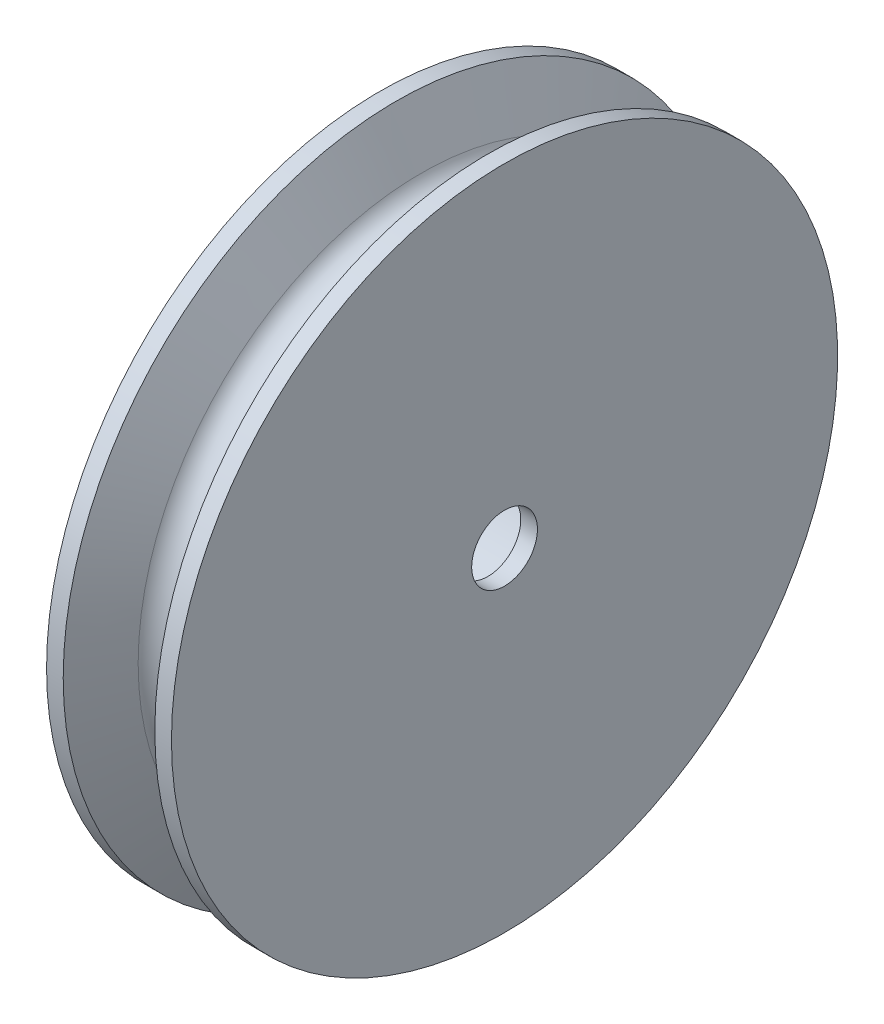
SolidWorks part; units mm, degrees
ref_plane "Alzado" through (0, 0, 0) normal (0, 0, 1) x (1, 0, 0)
ref_plane "Planta" through (0, 0, 0) normal (0, 1, 0) x (1, 0, 0)
ref_plane "Vista lateral" through (0, 0, 0) normal (1, 0, 0) x (0, 0, -1)
sketch "Croquis1" plane through (0, 0, 0) normal (0, 0, 1) x (1, 0, 0)
  line L0 (5.9522, 19.7456) -> (7.9522, 19.7456)
  line L1 (-7.0478, 19.7456) -> (-5.0478, 19.7456)
  line L2 (-7.0478, 19.7456) -> (-7.0478, -20.2544)
  line L3 (-7.0478, -20.2544) -> (7.9522, -20.2544)
  line L4 (7.9522, 19.7456) -> (7.9522, -20.2544)
  line L5 (-20.8444, -20.2544) -> (16.9874, -20.2544) construction
  line L7 (-7.0478, 19.7456) -> (-5.0478, 19.7456)
  line L8 (7.9522, 19.7456) -> (5.9522, 19.7456)
  line L9 (-5.0478, 19.7456) -> (-2.0478, 13.7456)
  line L11 (5.9522, 19.7456) -> (2.9522, 13.7456)
  arc A0 (2.9522, 13.7456) -> (-2.0478, 13.7456) centre (0.4522, 14.9085) cw
  point P0 (0, 0)
  dimension "D1" = 15
  dimension "D2" = 40
  dimension "D3" = 2
  dimension "D4" = 2
revolve "Revolución1" add sketch "Croquis1" angle 360 about L5
sketch "Croquis2" plane through (-7.0478, 0, 0) normal (-1, 0, 0) x (0, 0, 1)
  circle A0 centre (0, -20.2544) radius 3.95
  dimension "D1" = 7.9
extrude "Cortar-Extruir1" cut sketch "Croquis2" against normal blind 62
sketch "Croquis3" plane through (-7.0478, 0, 0) normal (-1, 0, 0) x (0, 0, 1)
  circle A0 centre (0, -20.2544) radius 10.95
  dimension "D1" = 21.9
extrude "Cortar-Extruir2" cut sketch "Croquis3" against normal blind 13
